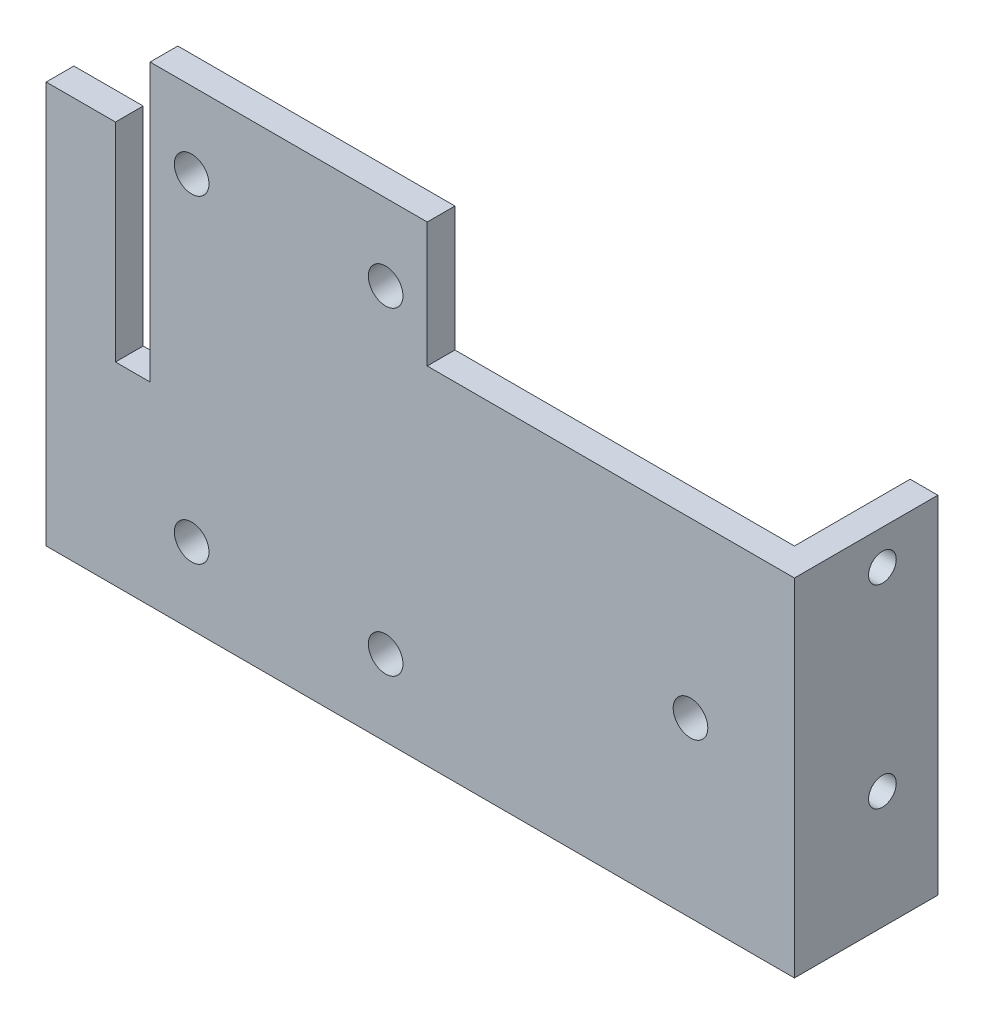
SolidWorks part; units mm, degrees
ref_plane "Спереди" through (0, 0, 0) normal (0, 0, 1) x (1, 0, 0)
ref_plane "Сверху" through (0, 0, 0) normal (0, 1, 0) x (1, 0, 0)
ref_plane "Справа" through (0, 0, 0) normal (1, 0, 0) x (0, 0, -1)
sketch "Эскиз1" plane through (0, 0, 0) normal (0, 0, 1) x (1, 0, 0)
  line L0 (35, 68) -> (35, 0) construction
  line L1 (0, 0) -> (108, 0)
  line L2 (0, 0) -> (0, 68)
  line L3 (0, 68) -> (55, 68)
  line L4 (108, 0) -> (108, 50)
  line L5 (21, 68) -> (21, 0) construction
  line L6 (55, 68) -> (55, 50)
  line L7 (55, 50) -> (108, 50)
  line L8 (49, 68) -> (49, 0) construction
  circle A0 centre (21, 57) radius 2.5
  circle A1 centre (49, 57) radius 2.5
  circle A2 centre (21, 11) radius 2.5
  circle A3 centre (49, 11) radius 2.5
  circle A4 centre (93, 25) radius 2.5
  dimension "D8" = 5
  dimension "D9" = 5
  dimension "D10" = 5
  dimension "D11" = 5
  dimension "D18" = 5
  dimension "D1" = 108
  dimension "D2" = 68
  dimension "D3" = 55
  dimension "D4" = 50
  dimension "D5" = 35
  dimension "D6" = 14
  dimension "D7" = 14
  dimension "D12" = 46
  dimension "D13" = 46
  dimension "D14" = 11
  dimension "D15" = 11
  dimension "D16" = 15
  dimension "D17" = 25
extrude "Бобышка-Вытянуть1" add sketch "Эскиз1" along normal blind 4
sketch "Эскиз2" plane through (0, 0, 4) normal (0, 0, 1) x (1, 0, 0)
  line L0 (0, 0) -> (108, 0) construction
  line L1 (108, 50) -> (104, 50)
  line L2 (108, 50) -> (108, 0)
  line L3 (108, 0) -> (104, 0)
  line L4 (104, 50) -> (104, 0)
  dimension "D1" = 4
extrude "Бобышка-Вытянуть2" add sketch "Эскиз2" against normal blind 20.7
sketch "Эскиз3" plane through (108, 0, 0) normal (1, 0, 0) x (0, 0, -1)
  line L0 (16.7, 0) -> (16.7, 50) construction
  line L3 (-4, 50) -> (16.7, 50) construction
  circle A0 centre (8.7, 45) radius 2
  circle A1 centre (8.7, 17) radius 2
  dimension "D1" = 4
  dimension "D2" = 4
  dimension "D3" = 28
  dimension "D4" = 5
  dimension "D5" = 8
extrude "Вырез-Вытянуть1" cut sketch "Эскиз3" against normal blind 6.7
sketch "Эскиз4" plane through (0, 0, 0) normal (0, 0, -1) x (-1, 0, 0)
  line L1 (0, 68) -> (-15, 68)
  line L2 (0, 68) -> (0, 58)
  line L3 (0, 58) -> (-10, 58)
  line L4 (-15, 68) -> (-15, 48)
  line L6 (-15, 48) -> (-15, 28)
  line L7 (-15, 28) -> (-10, 28)
  line L8 (-10, 58) -> (-10, 28)
  dimension "D1" = 10
  dimension "D2" = 10
  dimension "D3" = 40
  dimension "D4" = 5
extrude "Вырез-Вытянуть2" cut sketch "Эскиз4" against normal blind 10
